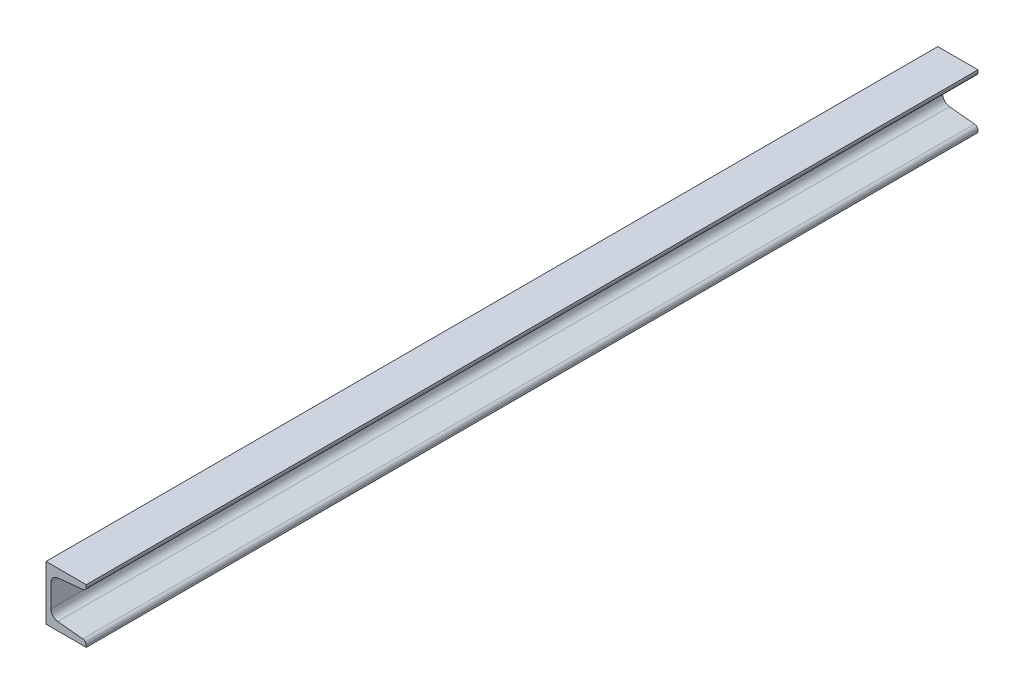
SolidWorks part; units mm, degrees
ref_plane "前视基准面" through (0, 0, 0) normal (0, 0, 1) x (1, 0, 0)
ref_plane "上视基准面" through (0, 0, 0) normal (0, 1, 0) x (1, 0, 0)
ref_plane "右视基准面" through (0, 0, 0) normal (1, 0, 0) x (0, 0, -1)
sketch "草图1" plane through (0, 0, 0) normal (0, 0, 1) x (1, 0, 0)
  line L0 (0, 0) -> (0, 50)
  line L1 (0, 0) -> (37, 0)
  line L2 (-55.9537, 25) -> (55.9537, 25) construction
  line L3 (0, 50) -> (37, 50)
  line L4 (4.5, 14.5099) -> (4.5, 35.2876)
  line L5 (16.25, -10) -> (16.25, 60) construction
  line L6 (10.8035, 7.5447) -> (33.8483, 5.2402)
  line L7 (37, 0) -> (37, 1.7575)
  line L8 (10.8035, 42.2529) -> (33.8483, 44.5574)
  line L9 (37, 48.04) -> (37, 50)
  arc A0 (10.8035, 42.2529) -> (4.5, 35.2876) centre (11.5, 35.2876) ccw
  arc A1 (4.5, 14.5099) -> (10.8035, 7.5447) centre (11.5, 14.5099) ccw
  arc A2 (33.8483, 44.5574) -> (37, 48.04) centre (33.5, 48.04) ccw
  arc A3 (37, 1.7575) -> (33.8483, 5.2402) centre (33.5, 1.7575) ccw
  point P7 (0, 25)
  point P11 (4.5, 25)
  point P14 (16.25, 25)
  point P15 (16.25, 7)
  point P17 (16.25, 43)
  point P19 (16.25, 43)
  point P20 (16.25, 7)
  point P23 (16.25, 43)
  dimension "D5" = 7
  dimension "D6" = 7
  dimension "D7" = 3.5
  dimension "D8" = 3.5
  dimension "h" = 50
  dimension "b" = 37
  dimension "d" = 4.5
  dimension "D1" = 16.25
  dimension "D2" = 7
  dimension "D3" = 5.711
  dimension "D4" = 5.711
extrude "凸台-拉伸1" add sketch "草图1" along normal blind 820
equation "\"高度\"= 50"
equation "\"腿宽\"= 37"
equation "\"腰宽\"= 4.5"
equation "\"h@草图1\"= \"高度\""
equation "\"d@草图1\"= \"腰宽\""
equation "\"D1@草图1\"= ( \"腿宽\" - \"腰宽\" ) / 2"
equation "\"平均腿厚\"= 7"
equation "\"内圆弧半径\"= 7"
equation "\"腿端圆弧半径\"= 3.5"
equation "\"D2@草图1\"= \"平均腿厚\""
equation "\"斜度\"= atn ( 0.1 )"
equation "\"D3@草图1\"= \"斜度\""
equation "\"D4@草图1\"= \"斜度\""
equation "\"D5@草图1\"= \"内圆弧半径\""
equation "\"D6@草图1\"= \"内圆弧半径\""
equation "\"D8@草图1\"= \"腿端圆弧半径\""
equation "\"D7@草图1\"= \"腿端圆弧半径\""
equation "\"b@草图1\"= \"腿宽\""
